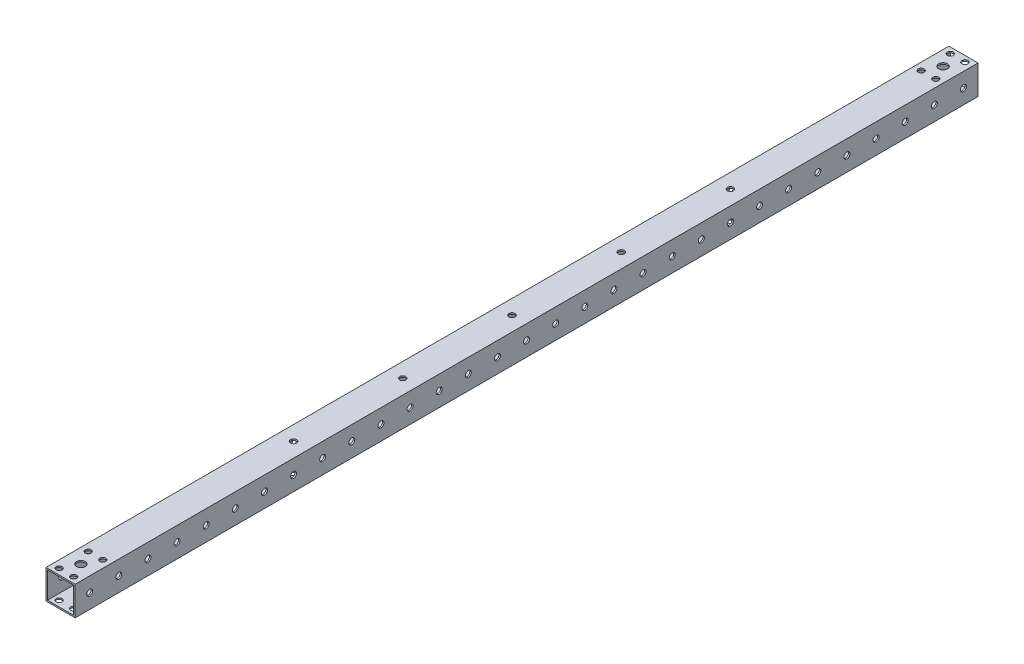
SolidWorks part; units mm, degrees
material "6061 合金"
ref_plane "前视基准面" through (0, 0, 0) normal (0, 0, 1) x (1, 0, 0)
ref_plane "上视基准面" through (0, 0, 0) normal (0, 1, 0) x (1, 0, 0)
ref_plane "右视基准面" through (0, 0, 0) normal (1, 0, 0) x (0, 0, -1)
other "Configuration Table"
sketch "草图1" plane through (0, 0, 0) normal (0, 0, 1) x (1, 0, 0)
  line L0 (-9, -9) -> (-9, 9)
  line L1 (-10, -10) -> (10, -10)
  line L2 (-10, -10) -> (-10, 10)
  line L3 (-10, 10) -> (10, 10)
  line L4 (10, -10) -> (10, 10)
  line L5 (-10, -10) -> (10, 10) construction
  line L6 (-10, 10) -> (10, -10) construction
  line L7 (-9, 9) -> (9, 9)
  line L8 (9, -9) -> (9, 9)
  line L9 (-9, -9) -> (9, -9)
  point P0 (0, 0)
  dimension "D1" = 20
  dimension "D2" = 1
extrude "凸台-拉伸1" add sketch "草图1" along normal mid plane 620
sketch "草图2" plane through (0, 10, 0) normal (0, 1, 0) x (1, 0, 0)
  line L0 (0, 0) -> (0, -50000) construction
  line L1 (10, -310) -> (-10, -310) construction
  line L2 (-5, -306) -> (5, -306) construction
  line L3 (-5, -306) -> (-5, -286) construction
  line L4 (-5, -286) -> (5, -286) construction
  line L5 (5, -306) -> (5, -286) construction
  line L6 (-5, -306) -> (5, -286) construction
  line L7 (-5, -286) -> (5, -306) construction
  line L8 (0, 0) -> (50000, 0) construction
  circle A0 centre (-5, -286) radius 2.025
  circle A1 centre (5, -286) radius 2.025
  circle A2 centre (-5, -306) radius 2.025
  circle A3 centre (5, -306) radius 2.025
  circle A4 centre (0, -296) radius 3.05
  circle A5 centre (5, 306) radius 2.025
  circle A6 centre (5, 286) radius 2.025
  circle A7 centre (-5, 286) radius 2.025
  circle A8 centre (0, 296) radius 3.05
  circle A9 centre (-5, 306) radius 2.025
  point P3 (0, -296)
  dimension "D3" = 4.05
  dimension "D4" = 6.1
  dimension "D1" = 10
  dimension "D2" = 20
  dimension "D5" = 4
extrude "切除-拉伸1" cut sketch "草图2" against normal blind 30
sketch "草图3" plane through (0, 10, 0) normal (0, 1, 0) x (1, 0, 0)
  line L0 (0, 150) -> (0, -150) construction
  circle A0 centre (0, 150) radius 2.1
  circle A1 centre (0, 75) radius 2.1
  circle A2 centre (0, 0) radius 2.1
  circle A3 centre (0, -75) radius 2.1
  circle A4 centre (0, -150) radius 2.1
  point P4 (0, 0)
  dimension "D2" = 5
  dimension "D3" = 4.2
  dimension "D1" = 300
extrude "切除-拉伸2" cut sketch "草图3" against normal blind 30
sketch "草图4" plane through (10, 0, 0) normal (1, 0, 0) x (0, 0, -1)
  line L0 (-310, 0) -> (310, 0) construction
  line L1 (-310, -10) -> (-310, 10) construction
  line L2 (310, -10) -> (310, 10) construction
  circle A0 centre (-300, 0) radius 2.05
  circle A1 centre (-280, 0) radius 2.05
  circle A2 centre (-260, 0) radius 2.05
  circle A3 centre (-240, 0) radius 2.05
  circle A4 centre (-220, 0) radius 2.05
  circle A5 centre (-200, 0) radius 2.05
  circle A6 centre (-180, 0) radius 2.05
  circle A7 centre (-160, 0) radius 2.05
  circle A8 centre (-140, 0) radius 2.05
  circle A9 centre (-120, 0) radius 2.05
  circle A10 centre (-100, 0) radius 2.05
  circle A11 centre (-80, 0) radius 2.05
  circle A12 centre (-60, 0) radius 2.05
  circle A13 centre (-40, 0) radius 2.05
  circle A14 centre (-20, 0) radius 2.05
  circle A15 centre (0, 0) radius 2.05
  circle A16 centre (20, 0) radius 2.05
  circle A17 centre (40, 0) radius 2.05
  circle A18 centre (60, 0) radius 2.05
  circle A19 centre (80, 0) radius 2.05
  circle A20 centre (100, 0) radius 2.05
  circle A21 centre (120, 0) radius 2.05
  circle A22 centre (140, 0) radius 2.05
  circle A23 centre (160, 0) radius 2.05
  circle A24 centre (180, 0) radius 2.05
  circle A25 centre (200, 0) radius 2.05
  circle A26 centre (220, 0) radius 2.05
  circle A27 centre (240, 0) radius 2.05
  circle A28 centre (260, 0) radius 2.05
  circle A29 centre (280, 0) radius 2.05
  circle A30 centre (300, 0) radius 2.05
  point P66 (299.3651, 0)
  point P69 (303.9397, 0)
  dimension "D1" = 4.1
  dimension "D4" = 10
  dimension "D2" = 10
  dimension "D3" = 31
extrude "切除-拉伸3" cut sketch "草图4" against normal mid plane 40
